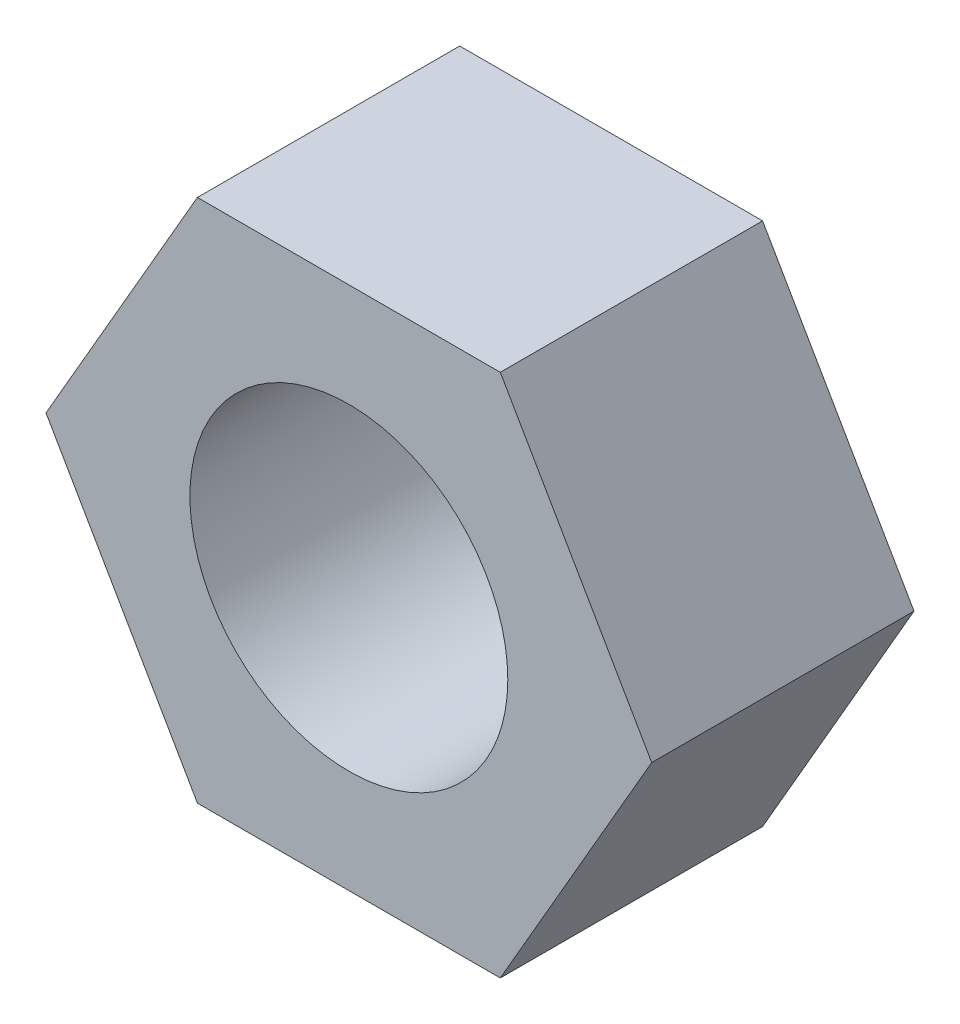
SolidWorks part; units mm, degrees
ref_plane "Front Plane" through (0, 0, 0) normal (0, 0, 1) x (1, 0, 0)
ref_plane "Top Plane" through (0, 0, 0) normal (0, 1, 0) x (1, 0, 0)
ref_plane "Right Plane" through (0, 0, 0) normal (1, 0, 0) x (0, 0, -1)
sketch "S01 - M6 hex nut AF10" plane through (0, 0, 0) normal (0, 0, 1) x (1, 0, 0)
  line L0 (5.7735, 0) -> (2.8868, 5)
  line L1 (2.8868, 5) -> (-2.8868, 5)
  line L2 (-2.8868, 5) -> (-5.7735, 0)
  line L3 (-5.7735, 0) -> (-2.8868, -5)
  line L4 (-2.8868, -5) -> (2.8868, -5)
  line L5 (2.8868, -5) -> (5.7735, 0)
  circle A0 centre (0, 0) radius 3.03
  dimension "D1" = 6.06
  dimension "D2" = 2.8868
  dimension "D3" = 5.7735
  dimension "D4" = 2.8868
  dimension "D5" = 5.7735
  dimension "D6" = 5
  dimension "D7" = 5
extrude "01 - M6 hex nut AF10" add sketch "S01 - M6 hex nut AF10" along normal blind 5
